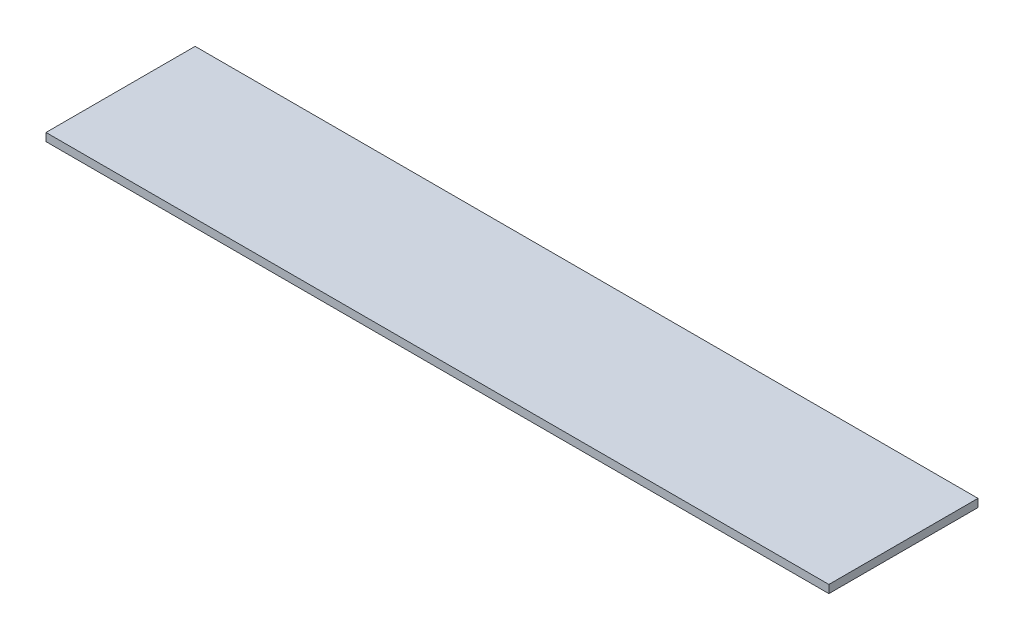
SolidWorks part; units mm, degrees
material "Pine"
ref_plane "Front Plane" through (0, 0, 0) normal (0, 0, 1) x (1, 0, 0)
ref_plane "Top Plane" through (0, 0, 0) normal (0, 1, 0) x (1, 0, 0)
ref_plane "Right Plane" through (0, 0, 0) normal (1, 0, 0) x (0, 0, -1)
sketch "Sketch1" plane through (0, 0, 0) normal (0, 1, 0) x (1, 0, 0)
  line L1 (933.45, -177.8) -> (-933.45, -177.8)
  line L2 (933.45, -177.8) -> (933.45, 177.8)
  line L3 (933.45, 177.8) -> (-933.45, 177.8)
  line L4 (-933.45, -177.8) -> (-933.45, 177.8)
  line L5 (933.45, -177.8) -> (-933.45, 177.8) construction
  line L6 (933.45, 177.8) -> (-933.45, -177.8) construction
  point P0 (0, 0)
  dimension "D1" = 1866.9
  dimension "D2" = 355.6
extrude "Boss-Extrude1" add sketch "Sketch1" along normal blind 19.05
